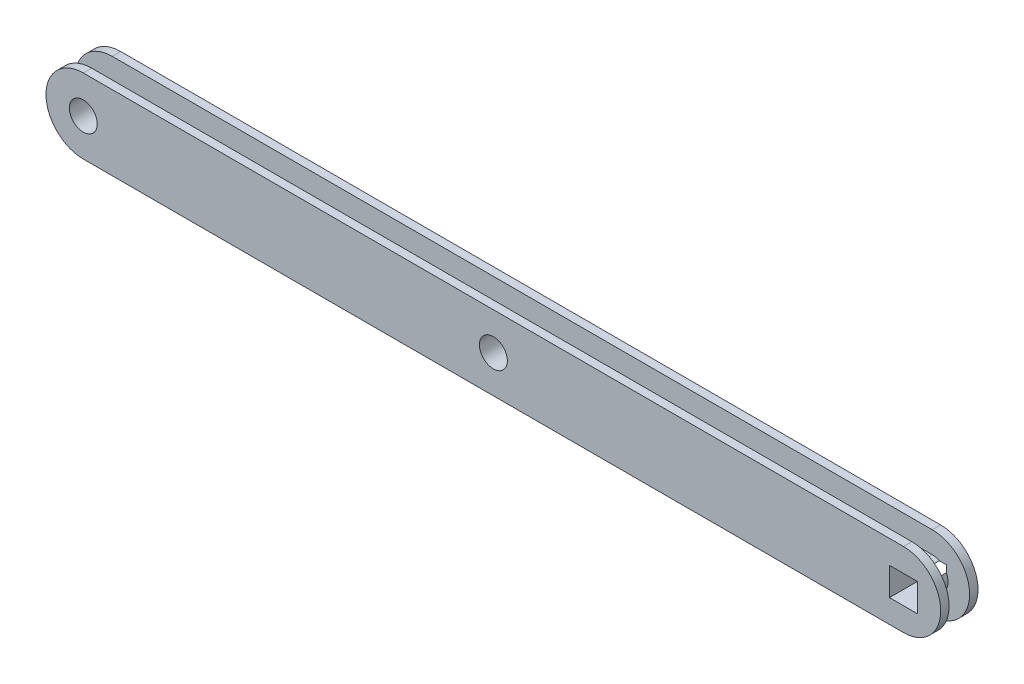
SolidWorks part; units mm, degrees
ref_plane "Plan de face" through (0, 0, 0) normal (0, 0, 1) x (1, 0, 0)
ref_plane "Plan de dessus" through (0, 0, 0) normal (0, 1, 0) x (1, 0, 0)
ref_plane "Plan de droite" through (0, 0, 0) normal (1, 0, 0) x (0, 0, -1)
sketch "Esquisse1" plane through (0, 0, 0) normal (0, 0, 1) x (1, 0, 0)
  line L4 (0, 0) -> (-152.4, 0)
  line L5 (-152.4, 0) -> (-152.4, 12.7)
  line L6 (-152.4, 12.7) -> (0, 12.7)
  line L7 (0, 12.7) -> (0, 0)
  dimension "D1" = 12.7
  dimension "D2" = 152.4
extrude "Boss.-Extru.1" add sketch "Esquisse1" against normal blind 6.35
sketch "Esquisse2" plane through (0, 0, 0) normal (0, 0, 1) x (1, 0, 0)
  line L0 (0, 12.7) -> (-152.4, 12.7) construction
  line L1 (-152.4, 0) -> (0, 0) construction
  line L2 (-152.4, 12.7) -> (-152.4, 0) construction
  line L3 (-6.35, 12.7) -> (0, 12.7)
  line L4 (0, 12.7) -> (0, 0)
  line L5 (0, 0) -> (0, 12.7) construction
  line L6 (0, 0) -> (-6.35, 0)
  line L7 (-146.05, 12.7) -> (-152.4, 12.7)
  line L8 (-152.4, 12.7) -> (-152.4, 0)
  line L9 (-152.4, 0) -> (-146.05, 0)
  line L11 (-8.7313, 3.9687) -> (-3.9688, 3.9687)
  line L12 (-8.7313, 3.9687) -> (-8.7313, 8.7312)
  line L13 (-8.7313, 8.7312) -> (-3.9688, 8.7312)
  line L14 (-3.9688, 3.9687) -> (-3.9688, 8.7312)
  line L15 (-8.7313, 3.9687) -> (-3.9688, 8.7312) construction
  line L16 (-8.7313, 8.7312) -> (-3.9688, 3.9687) construction
  circle A0 centre (-146.05, 6.35) radius 2.3813
  circle A1 centre (-6.35, 6.35) radius 2.3813
  circle A2 centre (-76.2, 6.35) radius 2.3813
  arc A3 (-146.05, 12.7) -> (-146.05, 0) centre (-146.05, 6.35) ccw
  arc A4 (-6.35, 12.7) -> (-6.35, 0) centre (-6.35, 6.35) cw
  line M1 (0, 0) -> (0, 12.7)
  line M2 (0, 12.7) -> (-152.4, 12.7)
  line M3 (-152.4, 12.7) -> (-152.4, 0)
  line M4 (-152.4, 0) -> (0, 0)
  dimension "D1" = 4.7625
  dimension "D4" = 4.7625
  dimension "D7" = 4.7625
  dimension "D2" = 6.35
  dimension "D3" = 6.35
  dimension "D5" = 6.35
  dimension "D6" = 6.35
  dimension "D8" = 69.85
  dimension "D9" = 4.7625
  dimension "D10" = 4.7625
extrude "Enlèv. mat.-Extru.1" cut sketch "Esquisse2" against normal through all contours A0 | A2 | A1 | A4 L4 M2 | A4 M1 M4 | A3 M2 M3 | A3 L8 M4 | A1 L13 L12 | A1 L14 L13 | A1 L11 L14 | A1 L12 L11
ref_plane "Plane1" through (0, 0, -3.175) normal (0, 0, 1) x (1, 0, 0)
ref_plane "Plane2" through (0, 6.35, 0) normal (0, 1, 0) x (1, 0, 0)
sketch "Sketch1" plane through (0, 6.35, 0) normal (0, 1, 0) x (1, 0, 0)
  line L0 (-146.05, 6.35) -> (-146.05, 0) construction
  line L1 (-6.35, 6.35) -> (-146.05, 6.35) construction
  line L2 (-6.35, 0) -> (-146.05, 0) construction
  line L3 (-146.05, 6.35) -> (-146.05, 0) construction
  line L4 (-148.4313, 6.35) -> (-148.4313, 0) construction
  line L5 (-146.05, 6.35) -> (-152.4, 6.35) construction
  line L6 (-152.4, 0) -> (-146.05, 0) construction
  line L7 (-152.4, 4.9225) -> (-150.5585, 4.9225)
  line L8 (-152.4, 6.35) -> (-152.4, 0) construction
  line L11 (-148.717, 4.9225) -> (-148.717, 1.4275)
  line L14 (-150.5585, 1.4275) -> (-152.4, 1.4275)
  line L15 (-152.4, 1.4275) -> (-152.4, 4.9225)
  line L16 (-150.5585, 4.9225) -> (-148.717, 4.9225)
  line L17 (-150.5585, 1.4275) -> (-148.717, 1.4275)
  line L18 (-152.4, 4.9225) -> (-166.5708, 4.9225)
  line L19 (-166.5708, 4.9225) -> (-166.5708, 1.4275)
  line L20 (-166.5708, 1.4275) -> (-152.4, 1.4275)
  point P18 (-148.4313, 3.175)
  point P21 (-148.717, 3.175)
  dimension "D1" = 2.3812
  dimension "D2" = 3.495
  dimension "D4" = 14.1708
  dimension "D5" = 1.8415
revolve "Cut-Revolve1" cut sketch "Sketch1" angle 180 mid plane about L0
ref_plane "Plane3" through (-76.2, 0, 0) normal (1, 0, 0) x (0, 0, -1)
mirror "Mirror1" about plane through (-76.2, 0, 0) normal (1, 0, 0) of "Cut-Revolve1"
sketch "Sketch2" plane through (0, 0, 0) normal (1, 0, 0) x (0, 0, -1)
  line L0 (1.4275, 9.017) -> (1.4275, 12.7) construction
  line L1 (1.4275, 9.017) -> (4.9225, 9.017)
  line L2 (1.4275, 9.017) -> (1.4275, 12.7)
  line L3 (1.4275, 12.7) -> (4.9225, 12.7)
  line L4 (4.9225, 9.017) -> (4.9225, 12.7)
  line L5 (4.9225, 12.7) -> (4.9225, 9.017) construction
  line L6 (4.9225, 12.7) -> (1.4275, 12.7) construction
  line L7 (4.9225, 9.017) -> (1.4275, 9.017) construction
  dimension "D1" = 3.495
extrude "Cut-Extrude1" cut sketch "Sketch2" against normal through all
mirror "Mirror2" about plane through (0, 6.35, 0) normal (0, 1, 0) of "Cut-Extrude1"
